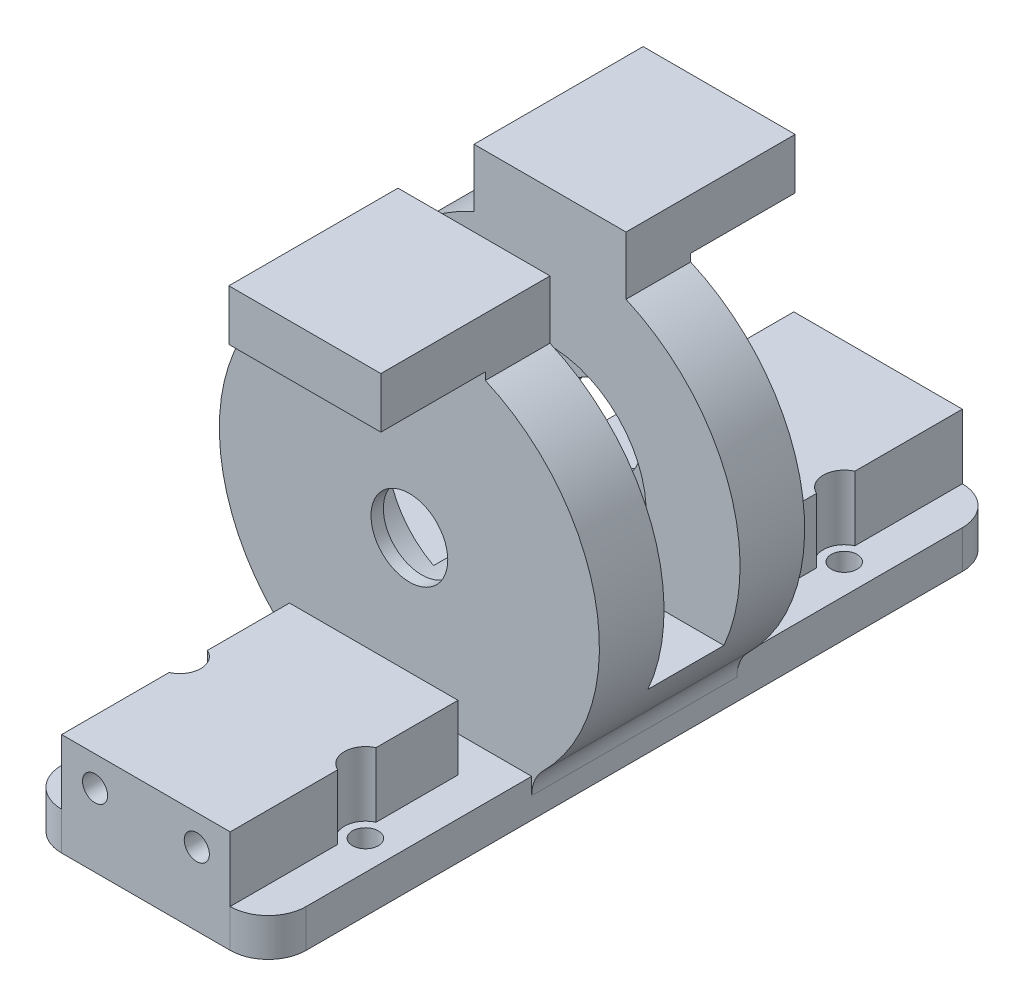
SolidWorks part; units mm, degrees
material "ABS"
ref_plane "Front Plane" through (0, 0, 0) normal (0, 0, 1) x (1, 0, 0)
ref_plane "Top Plane" through (0, 0, 0) normal (0, 1, 0) x (1, 0, 0)
ref_plane "Right Plane" through (0, 0, 0) normal (1, 0, 0) x (0, 0, -1)
sketch "Sketch1" plane through (0, 0, 0) normal (0, 0, 1) x (1, 0, 0)
  line L0 (10.625, 0.4) -> (47, 0.4)
  line L1 (47, 0.4) -> (47, 6.75)
  line L2 (47, 6.75) -> (12.7, 6.75)
  line L5 (0, 31.0549) -> (0, 68.3049) construction
  line L6 (-12.7, 6.75) -> (-47, 6.75)
  line L7 (-47, 6.75) -> (-47, 0.4)
  line L8 (-47, 0.4) -> (-10.625, 0.4)
  line L9 (11.7156, 0) -> (51.6651, 0) construction
  line L10 (0, 13.8049) -> (11.705, 13.8049) construction
  line L11 (-12.7, 69.8924) -> (12.7, 69.8924)
  line L12 (12.7, 6.75) -> (12.7, 69.8924)
  line L13 (-12.7, 6.75) -> (-12.7, 69.8924)
  line L14 (-10.625, 0.4) -> (10.625, 0.4)
  circle A3 centre (0, 31.0549) radius 6.4135
  arc A5 (-12.7, 60.1543) -> (-20.4288, 6.75) centre (0, 31.0549) ccw
  arc A6 (12.7, 60.1543) -> (20.4288, 6.75) centre (0, 31.0549) cw
  point P0 (0, 0.4)
  dimension "D2" = 69.4924
  dimension "D3" = 0.4
  dimension "D6" = 12.827
  dimension "D12" = 31.75
  dimension "D4" = 1.5875
  dimension "D5" = 17.25
  dimension "D7" = 6.35
  dimension "D8" = 36.375
  dimension "D9" = 37.25
  dimension "D10" = 25.4
  dimension "D11" = 21.25
extrude "Boss-Extrude1" add sketch "Sketch1" along normal blind 34.29
sketch "Sketch3" plane through (12.7, 0, 0) normal (1, 0, 0) x (0, 0, -1)
  line L1 (-23.495, 18.2499) -> (-10.795, 18.2499)
  line L4 (-10.795, 18.2499) -> (-10.795, 69.8924)
  line L5 (-23.495, 18.2499) -> (-10.795, 69.8924) construction
  line L6 (-23.495, 69.8924) -> (-10.795, 18.2499) construction
  line L9 (-34.29, 69.8924) -> (0, 69.8924) construction
  line L13 (-23.495, 69.8924) -> (-10.795, 69.8924)
  line L14 (-34.29, 69.8924) -> (0, 69.8924) construction
  line L15 (-23.495, 69.8924) -> (-23.495, 18.2499)
  point P4 (-17.145, 44.0711)
  point P9 (-17.145, 69.8924)
  point P14 (-17.145, 69.8924)
  dimension "D1" = 12.7
  dimension "D2" = 51.6425
extrude "Cut-Extrude1" cut sketch "Sketch3" against normal up to next and the other way up to next
sketch "Sketch5" plane through (0, 6.75, 0) normal (0, 1, 0) x (1, 0, 0)
  line L1 (-40, -6.35) -> (40, -6.35) construction
  line L2 (-40, -6.35) -> (-40, -27.94) construction
  line L3 (-40, -27.94) -> (40, -27.94) construction
  line L4 (40, -6.35) -> (40, -27.94) construction
  line L5 (-40, -6.35) -> (40, -27.94) construction
  line L6 (-40, -27.94) -> (40, -6.35) construction
  line L10 (47, -34.29) -> (20.4288, -34.29) construction
  line L11 (47, 0) -> (20.4288, 0) construction
  circle A0 centre (40, -27.94) radius 2.159
  circle A1 centre (40, -6.35) radius 2.159
  circle A2 centre (-40, -6.35) radius 2.159
  circle A3 centre (-40, -27.94) radius 2.159
  point P11 (0, -17.145)
  dimension "D1" = 4.318
  dimension "D2" = 6.35
  dimension "D3" = 6.35
  dimension "D4" = 40
extrude "Cut-Extrude2" cut sketch "Sketch5" against normal through all
sketch "Sketch6" plane through (0, 0, 34.29) normal (0, 0, 1) x (1, 0, 0)
  line L0 (0, 31.0549) -> (0, 68.3049) construction
  line L1 (-4.8514, 65.6525) -> (4.8514, 65.6525) construction
  line L2 (-12.7, 69.8924) -> (12.7, 69.8924)
  line L4 (-12.7, 61.4126) -> (12.7, 61.4126)
  line L5 (0, 65.6525) -> (0, 16.6305) construction
  line L6 (-6.6075, 41.1415) -> (10.2894, 41.1415) construction
  line L11 (12.7, 61.4126) -> (12.7, 69.8924)
  line L12 (-12.7, 61.4126) -> (-12.7, 69.8924)
  line L15 (-12.7, 69.8924) -> (12.7, 69.8924) construction
  line L16 (12.7, 60.1543) -> (12.7, 69.8924) construction
  circle A1 centre (0, 31.0549) radius 6.4135 construction
  circle A2 centre (4.8514, 65.6525) radius 1.5494 construction
  circle A3 centre (-4.8514, 65.6525) radius 1.5494 construction
  circle A4 centre (4.8514, 65.6525) radius 2 construction
  circle A11 centre (0, 31.0549) radius 6.4135 construction
  point P7 (0, 65.6525)
  point P23 (0, 41.1415)
  dimension "D4" = 3.0988
  dimension "D5" = 4
  dimension "D1" = 37.25
  dimension "D2" = 9.7028
  dimension "D3" = 2.6524
extrude "Boss-Extrude2" add sketch "Sketch6" along normal blind 17.4625
sketch "Sketch12" plane through (0, 0, 23.495) normal (0, 0, 1) x (1, 0, 0)
  circle A0 centre (0, 31.0549) radius 14.478
  dimension "D1" = 28.956
extrude "Cut-Extrude9" cut sketch "Sketch12" along normal blind 8.7312 and the other way blind 6.35
ref_plane "Plane1" through (0, 0, 17.145) normal (0, 0, -1) x (-1, 0, 0)
mirror "Mirror4" about plane through (0, 0, 17.145) normal (0, 0, -1) of "Cut-Extrude9", "Boss-Extrude2"
fillet "Fillet4" radius 6.35 4 edges at (-47, 3.575, 0) (-47, 3.575, 34.29) (47, 3.575, 0) (47, 3.575, 34.29)
chamfer "Chamfer1" distance 1.5875 angle 45 1 edges at (0, 45.5329, 10.795)
sketch "Sketch15" plane through (0, 6.75, 0) normal (0, 1, 0) x (1, 0, 0)
  line L0 (20.4288, 1.0134) -> (20.4288, -35.3034)
  line L1 (25.4, -34.29) -> (40.65, -34.29)
  line L2 (47, -27.94) -> (47, -6.35)
  line L3 (40.65, 0) -> (25.4, 0)
  line L4 (40.65, 0) -> (20.4288, 0) construction
  line L6 (0, -38.2208) -> (0, 38.2208) construction
  line L7 (-40.65, 0) -> (-25.4, 0)
  line L8 (-47, -27.94) -> (-47, -6.35)
  line L9 (-25.4, -34.29) -> (-40.65, -34.29)
  line L10 (-20.4288, 1.0134) -> (-20.4288, -35.3034)
  arc A1 (40.65, -34.29) -> (47, -27.94) centre (40.65, -27.94) ccw
  arc A2 (47, -6.35) -> (40.65, 0) centre (40.65, -6.35) ccw
  arc A3 (20.4288, 1.0134) -> (25.4, 0) centre (25.4, 12.7) ccw construction
  arc A4 (25.4, 0) -> (20.4288, 1.0134) centre (25.4, 12.7) cw
  arc A5 (20.4288, -35.3034) -> (25.4, -34.29) centre (25.4, -46.99) cw
  arc A6 (-20.4288, -35.3034) -> (-25.4, -34.29) centre (-25.4, -46.99) ccw
  arc A7 (-25.4, 0) -> (-20.4288, 1.0134) centre (-25.4, 12.7) ccw
  arc A8 (-47, -6.35) -> (-40.65, 0) centre (-40.65, -6.35) cw
  arc A9 (-40.65, -34.29) -> (-47, -27.94) centre (-40.65, -27.94) cw
extrude "Cut-Extrude13" cut sketch "Sketch15" against normal through all
ref_plane "Plane2" through (0, 0, 17.145) normal (0, 0, -1) x (-1, 0, 0)
sketch "Sketch16" plane through (0, 0, 17.145) normal (0, 0, -1) x (-1, 0, 0)
  line L0 (-20.4288, 4.7082) -> (-20.4288, 0.4) construction
  line L1 (-20.4288, 6.75) -> (20.4288, 6.75)
  line L2 (-20.4288, 6.75) -> (-20.4288, 0.4)
  line L3 (-20.4288, 0.4) -> (20.4288, 0.4)
  line L4 (20.4288, 6.75) -> (20.4288, 0.4)
  line L5 (-20.4288, 6.75) -> (20.4288, 0.4) construction
  line L6 (-20.4288, 0.4) -> (20.4288, 6.75) construction
  point P0 (0, 3.575)
extrude "Boss-Extrude3" add sketch "Sketch16" along normal mid plane 122.32
sketch "Sketch17" plane through (0, 0.4, 0) normal (0, -1, 0) x (1, 0, 0)
  line L0 (-28.4034, 17.145) -> (28.4034, 17.145) construction
  line L1 (-15.5, -22.855) -> (15.5, -22.855) construction
  line L2 (-15.5, -22.855) -> (-15.5, 57.145) construction
  line L3 (-15.5, 57.145) -> (15.5, 57.145) construction
  line L4 (15.5, -22.855) -> (15.5, 57.145) construction
  line L5 (-15.5, -22.855) -> (15.5, 57.145) construction
  line L6 (-15.5, 57.145) -> (15.5, -22.855) construction
  circle A0 centre (15.5, 57.145) radius 2.159
  circle A1 centre (-15.5, 57.145) radius 2.159
  circle A2 centre (15.5, -22.855) radius 2.159
  circle A3 centre (-15.5, -22.855) radius 2.159
  point P0 (0, 17.145)
  dimension "D3" = 4.318
  dimension "D1" = 80
  dimension "D2" = 31
extrude "Cut-Extrude14" cut sketch "Sketch17" against normal up to surface (6.35 mm away) up to face at (0, 6.75, 56.2975)
fillet "Fillet5" radius 6.35 6 edges at (-20.4288, 6.75, 17.145) (20.4288, 6.75, 17.145) (-20.4288, 3.575, -44.015) (20.4288, 3.575, -44.015) (-20.4288, 3.575, 78.305) (20.4288, 3.575, 78.305)
sketch "Sketch18" plane through (0, 6.75, 0) normal (0, 1, 0) x (1, 0, 0)
  line L1 (-14.0788, -78.305) -> (14.0788, -78.305)
  line L2 (-14.0788, -78.305) -> (-14.0788, -40.245)
  line L3 (-14.0788, -40.245) -> (14.0788, -40.245)
  line L4 (14.0788, -78.305) -> (14.0788, -40.245)
  dimension "D1" = 38.06
extrude "Boss-Extrude4" add sketch "Sketch18" along normal blind 10.8
mirror "Mirror5" about plane through (0, 0, 17.145) normal (0, 0, -1) of "Boss-Extrude4"
sketch "Sketch19" plane through (0, 0, -44.015) normal (0, 0, -1) x (-1, 0, 0)
  line L0 (-8.5, 17.55) -> (8.5, 17.55)
  line L1 (14.0788, 17.55) -> (-14.0788, 17.55) construction
  line L2 (8.5, 17.55) -> (8.5, 12.5549)
  line L3 (0, 17.55) -> (0, 15.1447)
  circle A0 centre (8.5, 12.5549) radius 2.1
  circle A1 centre (-8.5, 12.5549) radius 2.1
  point P5 (0, 17.55)
  dimension "D2" = 4.2
  dimension "D1" = 4.9951
extrude "Cut-Extrude15" cut sketch "Sketch19" against normal blind 40
mirror "Mirror6" about plane through (0, 0, 17.145) normal (0, 0, -1) of "Cut-Extrude15"
sketch "Sketch21" plane through (0, 6.75, 0) normal (0, 1, 0) x (1, 0, 0)
  circle A0 centre (15.5, -57.145) radius 3.5
  dimension "D1" = 7
extrude "Cut-Extrude16" cut sketch "Sketch21" along normal blind 11
sketch "Sketch22" plane through (0, 6.75, 0) normal (0, 1, 0) x (1, 0, 0)
  circle A0 centre (-15.5, -57.145) radius 3.5
  dimension "D1" = 7
extrude "Cut-Extrude17" cut sketch "Sketch22" along normal blind 11
mirror "Mirror7" about plane through (0, 0, 17.145) normal (0, 0, -1) of "Cut-Extrude16", "Cut-Extrude17"
equation "\"D3@Sketch5\"=\"D2@Sketch5\""
